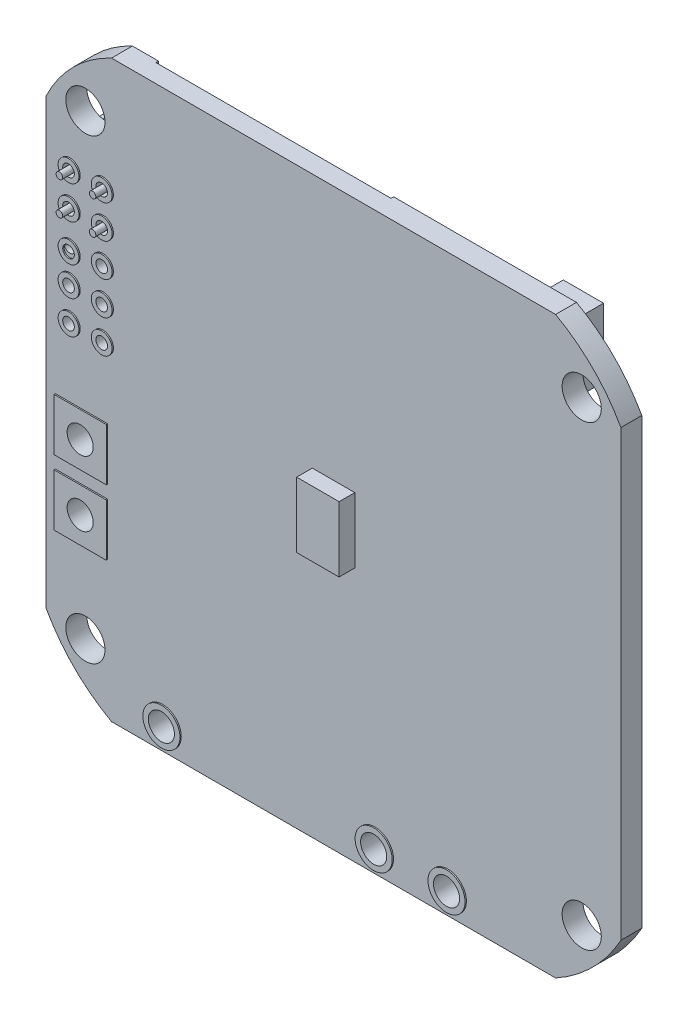
SolidWorks part; units mm, degrees
material "6061-T6 (SS)"
ref_plane "Alzado" through (0, 0, 0) normal (0, 0, 1) x (1, 0, 0)
ref_plane "Planta" through (0, 0, 0) normal (0, 1, 0) x (1, 0, 0)
ref_plane "Vista lateral" through (0, 0, 0) normal (1, 0, 0) x (0, 0, -1)
sketch "Croquis1" plane through (0, 0, 0) normal (0, 0, 1) x (1, 0, 0)
  line L0 (-22, 17) -> (-22, -17)
  line L1 (0, 0) -> (0, -6.2515) construction
  line L2 (22, 17) -> (22, -17)
  line L3 (-17, -22) -> (17, -22)
  line L4 (0, 0) -> (8.2976, 0) construction
  line L5 (-17, 22) -> (17, 22)
  arc A0 (-17, 22) -> (-22, 17) centre (-12.5089, 12.5089) ccw
  arc A2 (17, -22) -> (22, -17) centre (10.8379, -10.8379) ccw
  arc A3 (-22, -17) -> (-17, -22) centre (-10.8379, -10.8379) ccw
  arc A7 (22, 17) -> (17, 22) centre (10.8379, 10.8379) ccw
  point P0 (0, 0)
  point P4 (-22, 0)
  point P13 (0, -22)
  dimension "D3" = 21
  dimension "D4" = 34
  dimension "D1" = 34
  dimension "D2" = 22
  dimension "D5" = 22
extrude "Saliente-Extruir1" add sketch "Croquis1" along normal mid plane 1.6
sketch "Croquis2" plane through (0, 0, 0.8) normal (0, 0, 1) x (1, 0, 0)
  line L1 (19, -17.5) -> (-19, -17.5) construction
  line L2 (19, -17.5) -> (19, 17.5) construction
  line L3 (19, 17.5) -> (-19, 17.5) construction
  line L4 (-19, -17.5) -> (-19, 17.5) construction
  line L5 (19, -17.5) -> (-19, 17.5) construction
  line L6 (19, 17.5) -> (-19, -17.5) construction
  circle A0 centre (-19, 17.5) radius 1.5
  circle A1 centre (19, 17.5) radius 1.5
  circle A2 centre (19, -17.5) radius 1.5
  circle A3 centre (-19, -17.5) radius 1.5
  point P0 (0, 0)
  dimension "D1" = 3
  dimension "D2" = 38
  dimension "D3" = 35
extrude "Cortar-Extruir1" cut sketch "Croquis2" against normal through all
sketch "Croquis3" plane through (0, 0, 0.8) normal (0, 0, 1) x (1, 0, 0)
  line L1 (-1.625, 2.5) -> (1.625, 2.5)
  line L2 (-1.625, 2.5) -> (-1.625, -2.5)
  line L3 (-1.625, -2.5) -> (1.625, -2.5)
  line L4 (1.625, 2.5) -> (1.625, -2.5)
  line L5 (-1.625, 2.5) -> (1.625, -2.5) construction
  line L6 (-1.625, -2.5) -> (1.625, 2.5) construction
  point P0 (0, 0)
  dimension "D1" = 5
  dimension "D2" = 3.25
extrude "Saliente-Extruir2" add sketch "Croquis3" along normal blind 1.2
sketch "Croquis4" plane through (0, 0, -0.8) normal (0, 0, -1) x (-1, 0, 0)
  line L0 (22, 17) -> (22, -17) construction
  line L1 (-17, 22) -> (17, 22) construction
  circle A0 centre (17.653, 13) radius 0.445
  circle A1 centre (20.193, 13) radius 0.445
  circle A2 centre (20.193, 10.46) radius 0.445
  circle A3 centre (20.193, 7.92) radius 0.445
  circle A4 centre (20.193, 5.38) radius 0.445
  circle A5 centre (20.193, 2.84) radius 0.445
  circle A6 centre (17.653, 10.46) radius 0.445
  circle A7 centre (17.653, 7.92) radius 0.445
  circle A8 centre (17.653, 5.38) radius 0.445
  circle A9 centre (17.653, 2.84) radius 0.445
  dimension "D1" = 0.89
  dimension "D3" = 1.807
  dimension "D4" = 9
  dimension "D5" = 2.54
  dimension "D2" = 5
extrude "Cortar-Extruir2" cut sketch "Croquis4" against normal through all
sketch "Croquis5" plane through (0, 0, 0) normal (0, 0, 1) x (1, 0, 0)
  line L0 (-17, -22) -> (17, -22) construction
  line L1 (-17.3, -2.4) -> (-21.3, -2.4)
  line L2 (-17.3, -2.4) -> (-17.3, -6.4)
  line L3 (-17.3, -6.4) -> (-21.3, -6.4)
  line L4 (-21.3, -2.4) -> (-21.3, -6.4)
  line L5 (-17.3, -2.4) -> (-21.3, -6.4) construction
  line L6 (-17.3, -6.4) -> (-21.3, -2.4) construction
  line L7 (-17.3, -7.4) -> (-21.3, -7.4)
  line L8 (-17.3, -7.4) -> (-17.3, -11.4)
  line L9 (-17.3, -11.4) -> (-21.3, -11.4)
  line L10 (-21.3, -7.4) -> (-21.3, -11.4)
  line L11 (-17.3, -7.4) -> (-21.3, -11.4) construction
  line L12 (-17.3, -11.4) -> (-21.3, -7.4) construction
  line L13 (-22, 17) -> (-22, -17) construction
  circle A0 centre (-17.653, 2.84) radius 0.7974
  circle A1 centre (-20.193, 2.84) radius 0.7974
  circle A2 centre (-20.193, 5.38) radius 0.7974
  circle A3 centre (-17.653, 5.38) radius 0.7974
  circle A4 centre (-17.653, 7.92) radius 0.7974
  circle A5 centre (-17.653, 10.46) radius 0.7974
  circle A6 centre (-20.193, 7.62) radius 0.7974
  circle A7 centre (-20.193, 10.46) radius 0.7974
  circle A8 centre (-17.653, 13) radius 0.7974
  circle A9 centre (-20.193, 13) radius 0.7974
  circle A10 centre (-17.653, 13) radius 0.445
  circle A11 centre (-20.193, 13) radius 0.445
  circle A12 centre (-20.193, 10.46) radius 0.445
  circle A13 centre (-17.653, 10.46) radius 0.445
  circle A14 centre (-17.653, 7.92) radius 0.445
  circle A15 centre (-20.193, 7.62) radius 0.445
  circle A16 centre (-20.193, 5.38) radius 0.445
  circle A17 centre (-17.653, 5.38) radius 0.445
  circle A18 centre (-17.653, 2.84) radius 0.445
  circle A19 centre (-20.193, 2.84) radius 0.445
  point P0 (-19.3, -4.4)
  point P5 (-19.3, -9.4)
  dimension "D1" = 4
  dimension "D2" = 4
  dimension "D3" = 5
  dimension "D4" = 4
  dimension "D5" = 4
  dimension "D6" = 12.6
  dimension "D7" = 2.7
extrude "Saliente-Extruir3" add sketch "Croquis5" along normal mid plane 1.8
sketch "Croquis6" plane through (0, 0, -0.9) normal (0, 0, -1) x (-1, 0, 0)
  line L0 (21.3, -2.4) -> (21.3, -6.4) construction
  line L1 (21.3, -7.4) -> (21.3, -11.4) construction
  circle A0 centre (19.3, -4.4) radius 1
  circle A1 centre (19.3, -9.4) radius 1
  point P6 (21.3, -4.4)
  point P9 (21.3, -9.4)
  dimension "D1" = 2
extrude "Cortar-Extruir3" cut sketch "Croquis6" against normal through all both and the other way through all
sketch "Croquis7" plane through (0, 0, -0.8) normal (0, 0, -1) x (-1, 0, 0)
  line L0 (17, -22) -> (-17, -22) construction
  line L1 (22, 17) -> (22, -17) construction
  circle A0 centre (-8.75, -20.32) radius 1
  circle A1 centre (-3.17, -20.32) radius 1
  circle A2 centre (13.08, -20.32) radius 1
  dimension "D1" = 2
  dimension "D2" = 1.68
  dimension "D3" = 5.58
  dimension "D4" = 16.25
  dimension "D5" = 8.92
extrude "Cortar-Extruir4" cut sketch "Croquis7" against normal blind 10
sketch "Croquis8" plane through (0, 0, -0.8) normal (0, 0, -1) x (-1, 0, 0)
  line L0 (-22, -17) -> (-22, 17) construction
  line L1 (-20.5, 13.45) -> (-17.5, 13.45)
  line L2 (-20.5, 13.45) -> (-20.5, 10.95)
  line L3 (-20.5, 10.95) -> (-17.5, 10.95)
  line L4 (-17.5, 13.45) -> (-17.5, 10.95)
  line L5 (-20.5, 10.275) -> (-17.5, 10.275)
  line L6 (-20.5, 10.275) -> (-20.5, 7.775)
  line L7 (-20.5, 7.775) -> (-17.5, 7.775)
  line L8 (-17.5, 10.275) -> (-17.5, 7.775)
  line L10 (-17, 22) -> (17, 22) construction
  point P8 (-19, 7.775)
  point P11 (-20.5, 12.2)
  point P12 (-20.5, 9.025)
  point P15 (-17.5, 12.2)
  dimension "D1" = 3
  dimension "D2" = 3
  dimension "D3" = 2.5
  dimension "D4" = 3.175
  dimension "D5" = 9.8
extrude "Saliente-Extruir4" add sketch "Croquis8" along normal blind 1.2
sketch "Croquis9" plane through (0, 0, -2) normal (0, 0, -1) x (-1, 0, 0)
  line L0 (-17.5, 13.45) -> (-20.5, 13.45) construction
  line L1 (-17.5, 7.775) -> (-17.5, 10.275) construction
  line L2 (-17.5, 10.95) -> (-17.5, 13.45) construction
  circle A0 centre (-19, 12.2) radius 0.75
  circle A1 centre (-19, 9.025) radius 0.75
  point P7 (-19, 13.45)
  point P10 (-17.5, 9.025)
  point P14 (-17.5, 12.2)
  dimension "D1" = 1.5
extrude "Saliente-Extruir5" add sketch "Croquis9" along normal blind 0.8
sketch "Croquis10" plane through (0, 0, -0.8) normal (0, 0, -1) x (-1, 0, 0)
  line L0 (-22, -17) -> (-22, 17) construction
  line L1 (-16, -14.25) -> (-11, -14.25)
  line L2 (-16, -14.25) -> (-16, -19.25)
  line L3 (-16, -19.25) -> (-11, -19.25)
  line L4 (-11, -14.25) -> (-11, -19.25)
  line L5 (17, -22) -> (-17, -22) construction
  line L6 (11.25, -12.2) -> (16.25, -12.2)
  line L7 (11.25, -12.2) -> (11.25, -17.2)
  line L8 (11.25, -17.2) -> (16.25, -17.2)
  line L9 (16.25, -12.2) -> (16.25, -17.2)
  line L10 (5.8877, -14.25) -> (10.8877, -14.25)
  line L11 (5.8877, -14.25) -> (5.8877, -19.25)
  line L12 (5.8877, -19.25) -> (10.8877, -19.25)
  line L13 (10.8877, -14.25) -> (10.8877, -19.25)
  line L14 (0.4343, -14.25) -> (5.4343, -14.25)
  line L15 (0.4343, -14.25) -> (0.4343, -19.25)
  line L16 (0.4343, -19.25) -> (5.4343, -19.25)
  line L17 (5.4343, -14.25) -> (5.4343, -19.25)
  line L18 (22, 17) -> (22, -17) construction
  line L19 (-4.9483, -12.2) -> (0.0517, -12.2)
  line L20 (-4.9483, -12.2) -> (-4.9483, -17.2)
  line L21 (-4.9483, -17.2) -> (0.0517, -17.2)
  line L22 (0.0517, -12.2) -> (0.0517, -17.2)
  line L23 (-10.5433, -12.2) -> (-5.5433, -12.2)
  line L24 (-10.5433, -12.2) -> (-10.5433, -17.2)
  line L25 (-10.5433, -17.2) -> (-5.5433, -17.2)
  line L26 (-5.5433, -12.2) -> (-5.5433, -17.2)
  dimension "D1" = 5
  dimension "D2" = 5
  dimension "D3" = 6
  dimension "D4" = 2.75
  dimension "D5" = 5
  dimension "D6" = 5
  dimension "D7" = 5
  dimension "D8" = 5
  dimension "D9" = 5
  dimension "D10" = 5
  dimension "D11" = 5.75
  dimension "D12" = 4.8
  dimension "D13" = 5
  dimension "D14" = 5
  dimension "D15" = 5
  dimension "D16" = 5
extrude "Saliente-Extruir6" add sketch "Croquis10" along normal blind 0.9
sketch "Croquis11" plane through (0, 0, -0.8) normal (0, 0, -1) x (-1, 0, 0)
  line L0 (-13.6529, -19.5225) -> (-10.4593, -19.5225)
  line L1 (-10.4593, -19.5225) -> (-9.8124, -18.8756)
  line L2 (-9.8124, -18.8756) -> (-7.529, -18.8756)
  line L3 (-7.529, -18.8756) -> (-7.1476, -19.257)
  line L4 (-7.1476, -19.257) -> (-7.1476, -21.3437)
  line L5 (-7.1476, -21.3437) -> (-7.529, -21.7251)
  line L6 (-7.529, -21.7251) -> (-13.8301, -21.7251)
  line L7 (-13.8301, -21.7251) -> (-14.1414, -21.4138)
  line L8 (-14.1414, -21.4138) -> (-14.1414, -20.011)
  line L9 (-14.1414, -20.011) -> (-13.6529, -19.5225)
  line L10 (8.1723, -19.5225) -> (11.1983, -19.5225)
  line L11 (11.1983, -19.5225) -> (12.0225, -18.6983)
  line L12 (12.0225, -18.6983) -> (14.2962, -18.6983)
  line L13 (14.2962, -18.6983) -> (14.7785, -19.1806)
  line L14 (14.7785, -19.1806) -> (14.7785, -21.2429)
  line L15 (14.7785, -21.2429) -> (14.2962, -21.7251)
  line L16 (14.2962, -21.7251) -> (7.9951, -21.7251)
  line L17 (7.9951, -21.7251) -> (7.6839, -21.4138)
  line L18 (7.6839, -21.4138) -> (7.6839, -20.011)
  line L19 (7.6839, -20.011) -> (8.1723, -19.5225)
  line L20 (2.2631, -20.011) -> (1.7746, -19.5225)
  line L21 (2.2631, -21.4138) -> (2.2631, -20.011)
  line L22 (1.9518, -21.7251) -> (2.2631, -21.4138)
  line L23 (-4.3493, -21.7251) -> (1.9518, -21.7251)
  line L24 (-4.7307, -21.3437) -> (-4.3493, -21.7251)
  line L25 (-4.7307, -19.257) -> (-4.7307, -21.3437)
  line L26 (-4.3493, -18.8756) -> (-4.7307, -19.257)
  line L27 (-2.0659, -18.8756) -> (-4.3493, -18.8756)
  line L28 (-1.4189, -19.5225) -> (-2.0659, -18.8756)
  line L29 (1.7746, -19.5225) -> (-1.4189, -19.5225)
  line L30 (-5.9391, -18.0693) -> (-5.9391, -23.1735) construction
  circle A0 centre (-8.75, -20.32) radius 1
  circle A1 centre (-3.17, -20.32) radius 1
  circle A2 centre (13.08, -20.32) radius 1
extrude "Saliente-Extruir7" add sketch "Croquis11" along normal blind 0.1
sketch "Croquis12" plane through (0, 0, -0.8) normal (0, 0, -1) x (-1, 0, 0)
  line L0 (-19.5752, -2.7898) -> (-13.4845, -8.8805)
  line L1 (-19.5752, -2.7898) -> (-13.4845, 3.301)
  line L2 (-13.4845, -8.8805) -> (-7.3937, -2.7898)
  line L3 (-13.4845, 3.301) -> (-7.3937, -2.7898)
  line L4 (17, -22) -> (-17, -22) construction
  dimension "D1" = 45
extrude "Saliente-Extruir8" add sketch "Croquis12" along normal blind 0.75
sketch "Croquis13" plane through (0, 0, -0.8) normal (0, 0, -1) x (-1, 0, 0)
  line L1 (-16.4217, 20.3319) -> (-13.3413, 20.3319)
  line L2 (-16.4217, 20.3319) -> (-16.4217, 15.0982)
  line L3 (-16.4217, 15.0982) -> (-13.3413, 15.0982)
  line L4 (-13.3413, 20.3319) -> (-13.3413, 15.0982)
extrude "Saliente-Extruir9" add sketch "Croquis13" along normal blind 2.65
sketch "Croquis14" plane through (0, 0, -0.8) normal (0, 0, -1) x (-1, 0, 0)
  line L1 (-12.0511, 17.4084) -> (-8.2311, 17.4084)
  line L2 (-12.0511, 17.4084) -> (-12.0511, 13.5884)
  line L3 (-12.0511, 13.5884) -> (-8.2311, 13.5884)
  line L4 (-8.2311, 17.4084) -> (-8.2311, 13.5884)
  dimension "D1" = 3.82
extrude "Saliente-Extruir10" add sketch "Croquis14" along normal blind 3
sketch "Croquis30" plane through (0, 0, 0.8) normal (0, 0, 1) x (1, 0, 0)
  circle A0 centre (-13.08, -20.32) radius 1.4199
  circle A1 centre (8.75, -20.32) radius 1.4199
  circle A2 centre (3.17, -20.32) radius 1.4199
  circle A3 centre (-13.08, -20.32) radius 1
  circle A4 centre (3.17, -20.32) radius 1
  circle A5 centre (8.75, -20.32) radius 1
extrude "Saliente-Extruir17" add sketch "Croquis30" along normal blind 0.1
sketch "Croquis29" plane through (0, 0, -0.8) normal (0, 0, -1) x (-1, 0, 0)
  line L0 (-17, 22) -> (17, 22) construction
  line L1 (10.5, 1.5) -> (14, 1.5)
  line L2 (10.5, 1.5) -> (10.5, 0)
  line L3 (10.5, 0) -> (14, 0)
  line L4 (14, 1.5) -> (14, 0)
  line L5 (10.5, -0.65) -> (14, -0.65)
  line L6 (10.5, -0.65) -> (10.5, -2.15)
  line L7 (10.5, -2.15) -> (14, -2.15)
  line L8 (14, -0.65) -> (14, -2.15)
  line L9 (2.75, 1.5) -> (6.25, 1.5)
  line L10 (2.75, 1.5) -> (2.75, 0)
  line L11 (2.75, 0) -> (6.25, 0)
  line L12 (6.25, 1.5) -> (6.25, 0)
  line L13 (22, 17) -> (22, -17) construction
  dimension "D1" = 3.5
  dimension "D2" = 1.5
  dimension "D3" = 0.65
  dimension "D4" = 3.5
  dimension "D5" = 20.5
  dimension "D6" = 11.5
  dimension "D7" = 7.75
extrude "Saliente-Extruir16" add sketch "Croquis29" along normal blind 0.5
chamfer "Chaflán1" distance 1 angle 45 4 edges at (12.0511, 17.4084, -2.3) (8.2311, 17.4084, -2.3) (12.0511, 13.5884, -2.3) (8.2311, 13.5884, -2.3)
sketch "Croquis31" plane through (0, 0, -0.8) normal (0, 0, -1) x (-1, 0, 0)
  line L0 (-17, 22) -> (17, 22) construction
  line L1 (-3, 22) -> (15, 22)
  line L2 (-3, 22) -> (-3, 2.65)
  line L3 (-3, 2.65) -> (15, 2.65)
  line L4 (15, 22) -> (15, 2.65)
  line L5 (22, 17) -> (22, -17) construction
  dimension "D1" = 19.35
  dimension "D2" = 18
  dimension "D3" = 7
extrude "Cortar-Extruir5" cut sketch "Croquis31" against normal blind 0.2
sketch "Croquis32" plane through (0, 0, -0.9) normal (0, 0, -1) x (-1, 0, 0)
  circle A0 centre (17.653, 13) radius 0.65
  circle A1 centre (20.193, 13) radius 0.65
  circle A2 centre (20.193, 10.46) radius 0.65
  circle A3 centre (17.653, 10.46) radius 0.65
  dimension "D1" = 1.3
extrude "Saliente-Extruir18" add sketch "Croquis32" along normal blind 1.6
sketch "Croquis33" plane through (0, 0, -0.9) normal (0, 0, 1) x (1, 0, 0)
  circle A0 centre (-20.193, 13) radius 0.25
  circle A1 centre (-17.653, 13) radius 0.25
  circle A2 centre (-17.653, 10.46) radius 0.25
  circle A3 centre (-20.193, 10.46) radius 0.25
  dimension "D1" = 0.5
extrude "Saliente-Extruir19" add sketch "Croquis33" along normal blind 2.5
sketch "Croquis34" plane through (0, 0, -2.5) normal (0, 0, -1) x (-1, 0, 0)
  line L0 (16.388, 14.1102) -> (16.388, 11.9202)
  line L1 (16.388, 11.9202) -> (16.8728, 11.735)
  line L2 (16.8728, 11.735) -> (18.4226, 11.735)
  line L3 (18.4226, 11.735) -> (18.918, 11.8898)
  line L4 (18.918, 11.8898) -> (18.918, 14.1102)
  line L5 (18.918, 14.1102) -> (18.4332, 14.265)
  line L6 (18.4332, 14.265) -> (16.8728, 14.265)
  line L7 (16.8728, 14.265) -> (16.388, 14.1102)
  line L8 (17.653, 13) -> (17.653, 14.4547) construction
  line L9 (17.653, 13) -> (15.9852, 13) construction
  line L10 (18.9656, 14.1102) -> (18.9656, 11.9202)
  line L11 (18.9656, 11.9202) -> (19.4505, 11.735)
  line L12 (19.4505, 11.735) -> (21.0002, 11.735)
  line L13 (21.0002, 11.735) -> (21.4956, 11.8898)
  line L14 (21.4956, 11.8898) -> (21.4956, 14.1102)
  line L15 (21.4956, 14.1102) -> (21.0108, 14.265)
  line L16 (21.0108, 14.265) -> (19.4505, 14.265)
  line L17 (19.4505, 14.265) -> (18.9656, 14.1102)
  line L18 (20.2306, 13) -> (20.2306, 14.4547) construction
  line L19 (20.2306, 13) -> (18.5628, 13) construction
  line L20 (18.9656, 11.529) -> (18.9656, 9.339)
  line L21 (18.9656, 9.339) -> (19.4505, 9.1538)
  line L22 (19.4505, 9.1538) -> (21.0002, 9.1538)
  line L23 (21.0002, 9.1538) -> (21.4956, 9.3086)
  line L24 (21.4956, 9.3086) -> (21.4956, 11.529)
  line L25 (21.4956, 11.529) -> (21.0108, 11.6838)
  line L26 (21.0108, 11.6838) -> (19.4505, 11.6838)
  line L27 (19.4505, 11.6838) -> (18.9656, 11.529)
  line L28 (20.2306, 10.4188) -> (20.2306, 11.8735) construction
  line L29 (20.2306, 10.4188) -> (18.5628, 10.4188) construction
  line L30 (16.388, 11.529) -> (16.388, 9.339)
  line L31 (16.388, 9.339) -> (16.8728, 9.1538)
  line L32 (16.8728, 9.1538) -> (18.4226, 9.1538)
  line L33 (18.4226, 9.1538) -> (18.918, 9.3086)
  line L34 (18.918, 9.3086) -> (18.918, 11.529)
  line L35 (18.918, 11.529) -> (18.4332, 11.6838)
  line L36 (18.4332, 11.6838) -> (16.8728, 11.6838)
  line L37 (16.8728, 11.6838) -> (16.388, 11.529)
  line L38 (17.653, 10.4188) -> (17.653, 11.8735) construction
  line L39 (17.653, 10.4188) -> (15.9852, 10.4188) construction
  circle A0 centre (17.653, 13) radius 0.65
  circle A1 centre (20.2306, 13) radius 0.64
  circle A2 centre (20.2306, 10.4188) radius 0.6641
  circle A3 centre (17.653, 10.4188) radius 0.64
  point P2 (17.653, 14.265)
  point P9 (18.918, 13)
  dimension "D1" = 2.53
  dimension "D2" = 2.53
  dimension "D3" = 2
  dimension "D4" = 2
extrude "Saliente-Extruir20" add sketch "Croquis34" along normal blind 3
